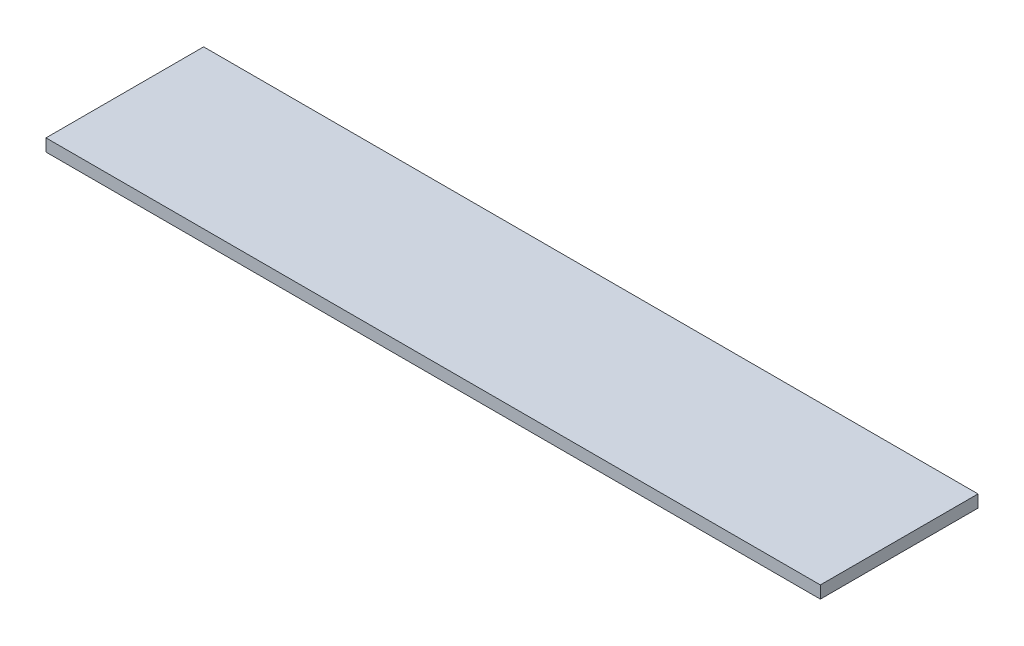
SolidWorks part; units mm, degrees
ref_plane "Спереди" through (0, 0, 0) normal (0, 0, 1) x (1, 0, 0)
ref_plane "Сверху" through (0, 0, 0) normal (0, 1, 0) x (1, 0, 0)
ref_plane "Справа" through (0, 0, 0) normal (1, 0, 0) x (0, 0, -1)
sketch "Эскиз1" plane through (0, 0, 0) normal (0, 0, 1) x (1, 0, 0)
  line L1 (-155.0828, 36.4367) -> (585.826, 36.4367)
  line L2 (-155.0828, 36.4367) -> (-155.0828, 48.2396)
  line L3 (-155.0828, 48.2396) -> (585.826, 48.2396)
  line L4 (585.826, 36.4367) -> (585.826, 48.2396)
extrude "Бобышка-Вытянуть1" add sketch "Эскиз1" along normal blind 150.8438
